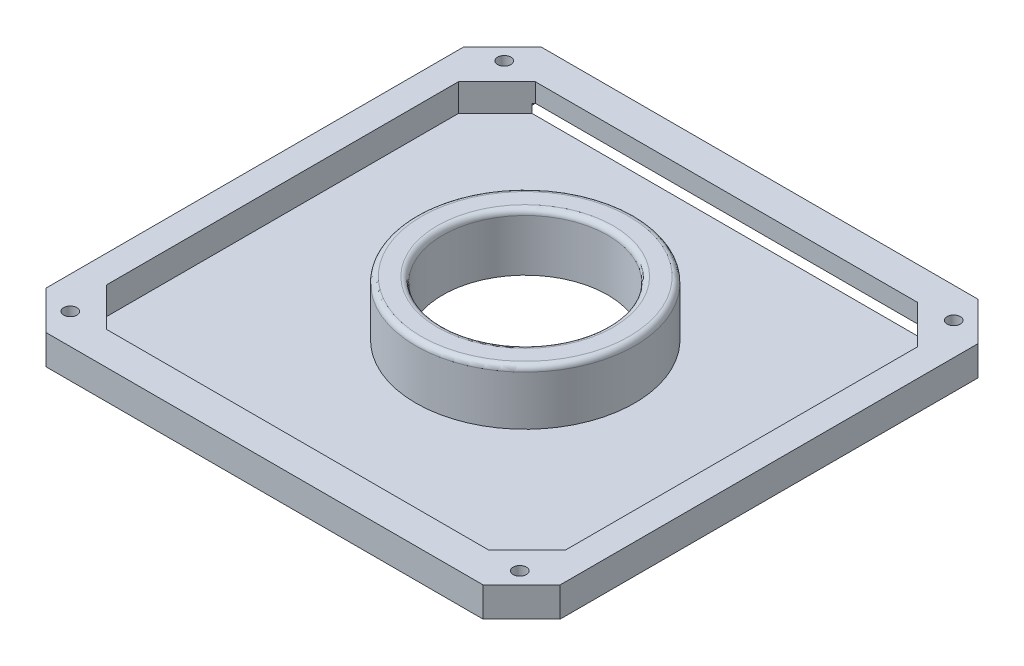
SolidWorks part; units mm, degrees
ref_plane "Front Plane" through (0, 0, 0) normal (0, 0, 1) x (1, 0, 0)
ref_plane "Top Plane" through (0, 0, 0) normal (0, 1, 0) x (1, 0, 0)
ref_plane "Right Plane" through (0, 0, 0) normal (1, 0, 0) x (0, 0, -1)
ref_plane "Plane1" through (0, 5.4, 0) normal (0, 1, 0) x (1, 0, 0)
sketch "Sketch1" plane through (0, 5.4, 0) normal (0, 1, 0) x (1, 0, 0)
  line L0 (-46.75, 45) -> (-46.75, -45)
  line L1 (-46.75, -45) -> (46.75, -45)
  line L2 (46.75, -45) -> (46.75, 45)
  line L3 (46.75, 45) -> (-46.75, 45)
extrude "Boss-Extrude1" add sketch "Sketch1" against normal blind 5.4
ref_plane "Plane2" through (0, 2, 0) normal (0, -1, 0) x (1, 0, 0)
sketch "Sketch2" plane through (0, 2, 0) normal (0, -1, 0) x (1, 0, 0)
  line L0 (-41.75, -39) -> (41.75, -39)
  line L1 (41.75, -39) -> (41.75, 39)
  line L2 (41.75, 39) -> (-41.75, 39)
  line L3 (-41.75, 39) -> (-41.75, -39)
extrude "Cut-Extrude1" cut sketch "Sketch2" against normal up to next
chamfer "Chamfer1" distance 7 angle 45 1 edges at (41.75, 3.7, -39)
chamfer "Chamfer2" distance 7 angle 45 1 edges at (41.75, 3.7, 39)
chamfer "Chamfer3" distance 7 angle 45 1 edges at (46.75, 2.7, 45)
chamfer "Chamfer4" distance 7 angle 45 1 edges at (46.75, 2.7, -45)
chamfer "Chamfer5" distance 7 angle 45 1 edges at (-46.75, 2.7, -45)
chamfer "Chamfer6" distance 7 angle 45 1 edges at (-41.75, 3.7, -39)
chamfer "Chamfer7" distance 7 angle 45 1 edges at (-46.75, 2.7, 45)
chamfer "Chamfer8" distance 7 angle 45 1 edges at (-41.75, 3.7, 39)
ref_plane "Plane3" through (0, 0.4, 0) normal (0, -1, 0) x (1, 0, 0)
sketch "Sketch3" plane through (0, 0.4, 0) normal (0, -1, 0) x (1, 0, 0)
  line L0 (-41.75, -32) -> (-35.0452, -38.7048)
  line L1 (-35.0452, -38.7048) -> (35.0452, -38.7048)
  line L2 (35.0452, -38.7048) -> (41.75, -32)
  line L3 (41.75, -32) -> (41.75, 32)
  line L4 (41.75, 32) -> (34.75, 39)
  line L5 (34.75, 39) -> (-34.75, 39)
  line L6 (-34.75, 39) -> (-41.75, 32)
  line L7 (-41.75, 32) -> (-41.75, -32)
extrude "Cut-Extrude2" cut sketch "Sketch3" against normal up to next
ref_plane "Plane4" through (-36.75, 0, 0) normal (-1, 0, 0) x (0, -1, 0)
sketch "Sketch4" plane through (-36.75, 0, 0) normal (-1, 0, 0) x (0, -1, 0)
  line L0 (-2, -45) -> (0, -45)
  line L1 (0, -45) -> (0, -38.7048)
  line L2 (0, -38.7048) -> (-2, -38.7048)
  line L3 (-2, -38.7048) -> (-2, -45)
extrude "Cut-Extrude3" cut sketch "Sketch4" against normal blind 73.5
ref_plane "Plane5" through (0, 10.4, 0) normal (0, 1, 0) x (1, 0, 0)
sketch "Sketch5" plane through (0, 10.4, 0) normal (0, 1, 0) x (1, 0, 0)
  circle A0 centre (0, 2.4048) radius 19.9
extrude "Boss-Extrude2" add sketch "Sketch5" against normal up to surface (10 mm away) up to face at (0, 0.4, 0.0738)
hole_wizard "#2 Clearance Hole1" positions "Sketch7" profile "Sketch6" hole size "#2" standard "ANSI Inch"
sketch "Sketch7" plane through (0, 5.4, 0) normal (0, 1, 0) x (1, 0, 0)
  point P0 (40.8712, -39.4579)
sketch "Sketch6" plane through (40.8712, 5.4, 39.4579) normal (1, 0, 0) x (0, 0, 1)
  line L0 (0, 0) -> (0, 5.4)
  line L1 (0, 5.4) -> (1.2, 5.4)
  line L2 (1.2, 5.4) -> (1.2, 0)
  line L5 (1.2, 0) -> (0, 0)
  line L11 (0, -6.35) -> (0, 107.95) construction
  dimension "Thru Hole Dia." = 2.4
  dimension "Thru Hole Depth" = 5.4
hole_wizard "#2 Clearance Hole2" positions "Sketch9" profile "Sketch8" hole size "#2" standard "ANSI Inch"
sketch "Sketch9" plane through (0, 5.4, 0) normal (0, 1, 0) x (1, 0, 0)
  point P0 (40.8712, 39.4579)
sketch "Sketch8" plane through (40.8712, 5.4, -39.4579) normal (1, 0, 0) x (0, 0, 1)
  line L0 (0, 0) -> (0, 5.4)
  line L1 (0, 5.4) -> (1.2, 5.4)
  line L2 (1.2, 5.4) -> (1.2, 0)
  line L5 (1.2, 0) -> (0, 0)
  line L11 (0, -6.35) -> (0, 107.95) construction
  dimension "Thru Hole Dia." = 2.4
  dimension "Thru Hole Depth" = 5.4
hole_wizard "#2 Clearance Hole3" positions "Sketch11" profile "Sketch10" hole size "#2" standard "ANSI Inch"
sketch "Sketch11" plane through (0, 5.4, 0) normal (0, 1, 0) x (1, 0, 0)
  point P0 (-40.8712, 39.4579)
sketch "Sketch10" plane through (-40.8712, 5.4, -39.4579) normal (1, 0, 0) x (0, 0, 1)
  line L0 (0, 0) -> (0, 5.4)
  line L1 (0, 5.4) -> (1.2, 5.4)
  line L2 (1.2, 5.4) -> (1.2, 0)
  line L5 (1.2, 0) -> (0, 0)
  line L11 (0, -6.35) -> (0, 107.95) construction
  dimension "Thru Hole Dia." = 2.4
  dimension "Thru Hole Depth" = 5.4
hole_wizard "#2 Clearance Hole4" positions "Sketch13" profile "Sketch12" hole size "#2" standard "ANSI Inch"
sketch "Sketch13" plane through (0, 5.4, 0) normal (0, 1, 0) x (1, 0, 0)
  point P0 (-40.8712, -39.4579)
sketch "Sketch12" plane through (-40.8712, 5.4, 39.4579) normal (1, 0, 0) x (0, 0, 1)
  line L0 (0, 0) -> (0, 5.4)
  line L1 (0, 5.4) -> (1.2, 5.4)
  line L2 (1.2, 5.4) -> (1.2, 0)
  line L5 (1.2, 0) -> (0, 0)
  line L11 (0, -6.35) -> (0, 107.95) construction
  dimension "Thru Hole Dia." = 2.4
  dimension "Thru Hole Depth" = 5.4
hole_wizard "Hole1" positions "Sketch15" profile "Sketch14" legacy
sketch "Sketch15" plane through (0, 10.4, 0) normal (0, 1, 0) x (1, 0, 0)
  point P0 (0, 2.4048)
sketch "Sketch14" plane through (0, 10.4, -2.4048) normal (1, 0, 0) x (0, 0, 1)
  line L0 (0, 0) -> (0, 10.4)
  line L1 (0, 10.4) -> (15, 10.4)
  line L2 (15, 10.4) -> (15, 0)
  line L3 (15, 0) -> (0, 0)
  line L4 (0, 110) -> (0, -10) construction
  dimension "Diameter" = 30
  dimension "Depth" = 10.4
fillet "Fillet1" radius 1 2 edges at (-36.75, 1, -38.7048) (36.75, 1, -38.7048)
fillet "Fillet2" radius 1 2 edges at (0, 10.4, -22.3048) (0, 10.4, 12.5952)
